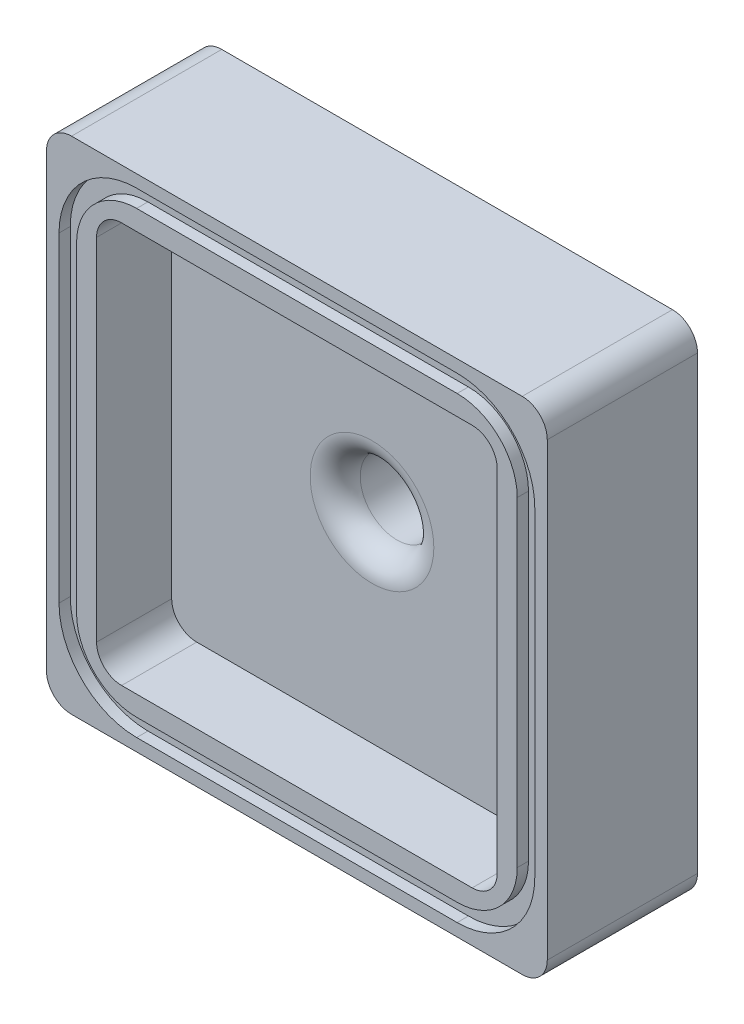
SolidWorks part; units mm, degrees
ref_plane "Front Plane" through (0, 0, 0) normal (0, 0, 1) x (1, 0, 0)
ref_plane "Top Plane" through (0, 0, 0) normal (0, 1, 0) x (1, 0, 0)
ref_plane "Right Plane" through (0, 0, 0) normal (1, 0, 0) x (0, 0, -1)
ref_plane "Plane1" through (0, 0, 30) normal (0, 0, 1) x (1, 0, 0)
sketch "Sketch1" plane through (0, 0, 30) normal (0, 0, 1) x (1, 0, 0)
  line L0 (100, 0) -> (100, 100)
  line L1 (100, 100) -> (0, 100)
  line L2 (0, 100) -> (0, 0)
  line L3 (0, 0) -> (100, 0)
extrude "Boss-Extrude1" add sketch "Sketch1" against normal blind 30
sketch "Sketch2" plane through (0, 0, 30) normal (0, 0, 1) x (1, 0, 0)
  line L0 (2.5, 2.5) -> (97.5, 2.5)
  line L1 (97.5, 2.5) -> (97.5, 97.5)
  line L2 (97.5, 97.5) -> (2.5, 97.5)
  line L3 (2.5, 97.5) -> (2.5, 2.5)
extrude "Cut-Extrude1" cut sketch "Sketch2" against normal blind 2.25
sketch "Sketch3" plane through (0, 0, 27.75) normal (0, 0, 1) x (1, 0, 0)
  line L0 (6, 6) -> (6, 94)
  line L1 (6, 94) -> (94, 94)
  line L2 (94, 94) -> (94, 6)
  line L3 (94, 6) -> (6, 6)
extrude "Boss-Extrude2" add sketch "Sketch3" along normal blind 2.25
sketch "Sketch4" plane through (0, 0, 30) normal (0, 0, 1) x (1, 0, 0)
  line L0 (10, 90) -> (10, 10)
  line L1 (10, 10) -> (90, 10)
  line L2 (90, 10) -> (90, 90)
  line L3 (90, 90) -> (10, 90)
extrude "Cut-Extrude2" cut sketch "Sketch4" against normal blind 15
hole_wizard "9/16 Clearance Hole1" positions "Sketch6" profile "Sketch5" hole size "9/16" standard "ANSI Inch"
sketch "Sketch6" plane through (0, 0, 15) normal (0, 0, 1) x (1, 0, 0)
  point P0 (50.0002, 49.9992)
sketch "Sketch5" plane through (50.0002, 49.9992, 15) normal (1, 0, 0) x (0, -1, 0)
  line L0 (0, 0) -> (0, 15)
  line L1 (0, 15) -> (7.35, 15)
  line L2 (7.35, 15) -> (7.35, 0)
  line L5 (7.35, 0) -> (0, 0)
  line L11 (0, -6.35) -> (0, 107.95) construction
  dimension "Thru Hole Dia." = 14.7
  dimension "Thru Hole Depth" = 15
hole_wizard "5/16 Clearance Hole1" positions "Sketch8" profile "Sketch7" hole size "5/16" standard "ANSI Inch"
sketch "Sketch8" plane through (0, 0, 0) normal (0, 0, -1) x (-1, 0, 0)
  point P0 (-80, 20)
sketch "Sketch7" plane through (80, 20, 0) normal (1, 0, 0) x (0, 1, 0)
  line L0 (0, 0) -> (0, 30)
  line L1 (0, 30) -> (4.35, 30)
  line L2 (4.35, 30) -> (4.35, 0)
  line L5 (4.35, 0) -> (0, 0)
  line L11 (0, -6.35) -> (0, 107.95) construction
  dimension "Thru Hole Dia." = 8.7
  dimension "Thru Hole Depth" = 30
fillet "Fillet1" radius 5 9 edges at (0, 0, 15) (10, 90, 22.5) (0, 100, 15) (90, 90, 22.5) (100, 0, 15) (10, 10, 22.5) (57.3502, 49.9992, 15) (90, 10, 22.5) (100, 100, 15)
fillet "Fillet2" radius 12 4 edges at (6, 6, 28.875) (6, 94, 28.875) (94, 94, 28.875) (94, 6, 28.875)
fillet "Fillet3" radius 15.5 4 edges at (97.5, 97.5, 28.875) (2.5, 2.5, 28.875) (97.5, 2.5, 28.875) (2.5, 97.5, 28.875)
